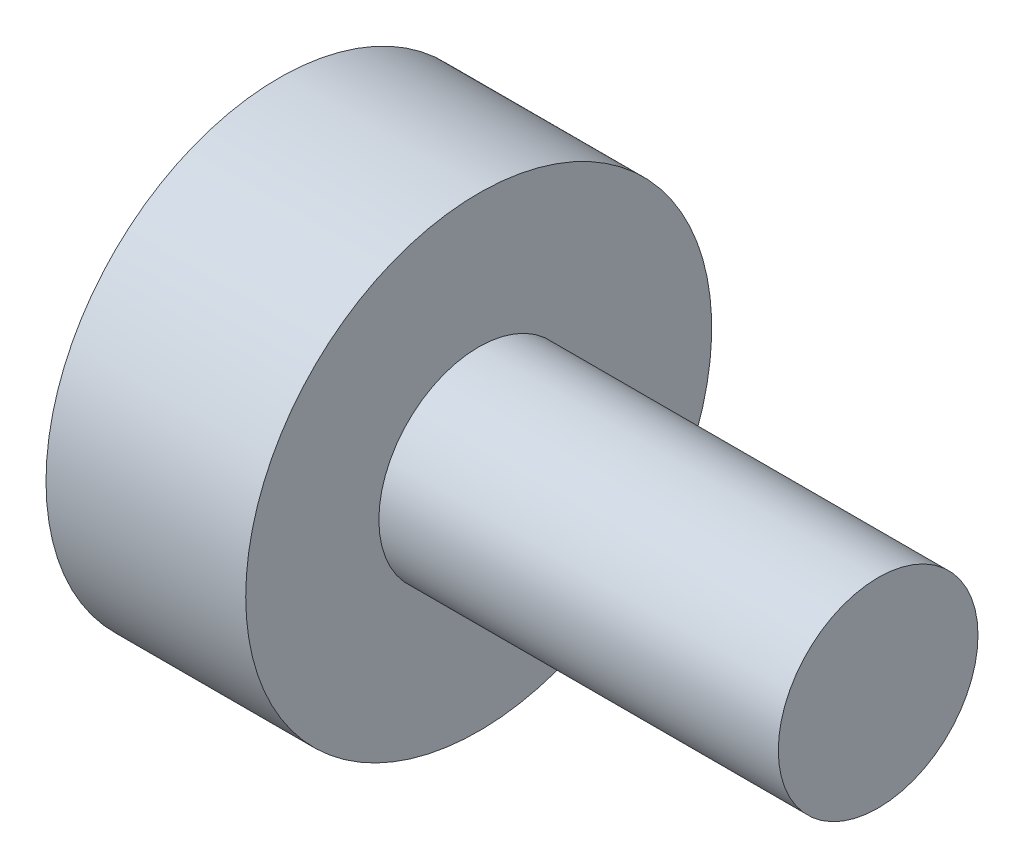
SolidWorks part; units mm, degrees
ref_plane "Спереди" through (0, 0, 0) normal (0, 0, 1) x (1, 0, 0)
ref_plane "Сверху" through (0, 0, 0) normal (0, 1, 0) x (1, 0, 0)
ref_plane "Справа" through (0, 0, 0) normal (1, 0, 0) x (0, 0, -1)
sketch "Эскиз1" plane through (0, 0, 0) normal (0, 0, 1) x (1, 0, 0)
  line L0 (0, 0) -> (100, 0)
  line L1 (0, 0) -> (0, 20)
  line L2 (0, 20) -> (10, 20)
  line L3 (10, 20) -> (10, 35)
  line L4 (10, 35) -> (40, 35)
  line L5 (40, 35) -> (40, 15)
  line L6 (40, 15) -> (100, 15)
  line L7 (100, 0) -> (100, 15)
revolve "Повернуть1" add sketch "Эскиз1" angle 360 about L0
ref_plane "Плоскость4" through (0, 0, 0) normal (1, 0, 0) x (0, 0, -1)
sketch "Эскиз2" plane through (0, 0, 0) normal (1, 0, 0) x (0, 0, -1)
  circle A0 centre (0, 10) radius 5
extrude "Вырез-Вытянуть1" cut sketch "Эскиз2" along normal blind 20
